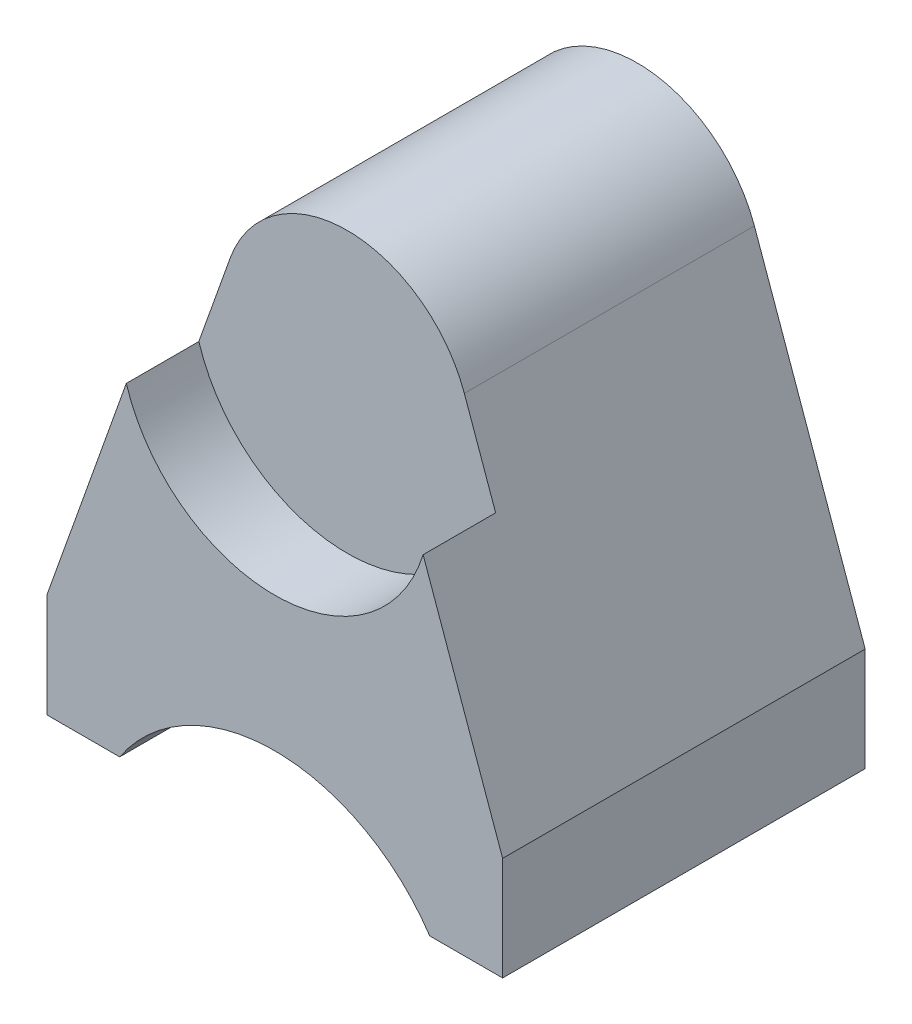
SolidWorks part; units mm, degrees
ref_plane "Front Plane" through (0, 0, 0) normal (0, 0, 1) x (1, 0, 0)
ref_plane "Top Plane" through (0, 0, 0) normal (0, 1, 0) x (1, 0, 0)
ref_plane "Right Plane" through (0, 0, 0) normal (1, 0, 0) x (0, 0, -1)
sketch "Sketch1" plane through (0, 0, 0) normal (0, 0, 1) x (1, 0, 0)
  line L0 (0, 72.4909) -> (0, -47.9455) construction
  line L1 (14.9666, 0) -> (22, 0)
  line L2 (-14.9666, 0) -> (-22, 0)
  line L3 (22, 0) -> (22, 10)
  line L4 (-22, 0) -> (-22, 10)
  line L5 (22, 10) -> (11.3042, 40.0267)
  line L6 (-22, 10) -> (-11.3042, 40.0267)
  arc A1 (-14.9666, 0) -> (14.9666, 0) centre (0, -10) cw
  arc A2 (11.3042, 40.0267) -> (-11.3042, 40.0267) centre (0, 36) ccw
  dimension "D1" = 18
  dimension "D2" = 12
  dimension "D3" = 46
  dimension "D4" = 10
  dimension "D5" = 44
  dimension "D6" = 10
extrude "Boss-Extrude1" add sketch "Sketch1" against normal mid plane 35
sketch "Sketch2" plane through (0, 0, 17.5) normal (0, 0, 1) x (1, 0, 0)
  circle A0 centre (0, 36) radius 15
  arc A1 (11.3042, 40.0267) -> (-11.3042, 40.0267) centre (0, 36) ccw construction
  dimension "D1" = 15
extrude "Cut-Extrude1" cut sketch "Sketch2" against normal blind 7
